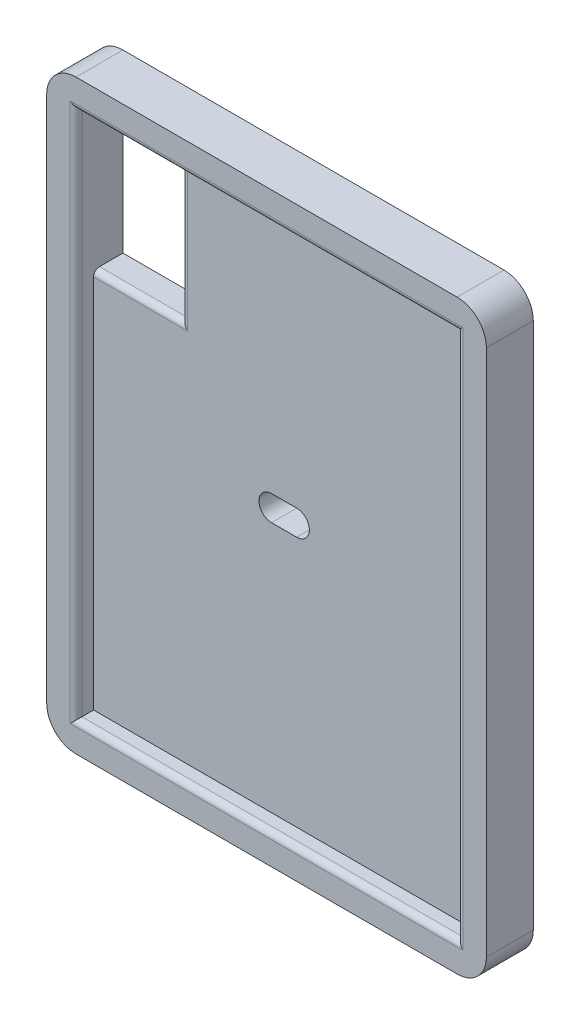
SolidWorks part; units mm, degrees
ref_plane "Front Plane" through (0, 0, 0) normal (1, 0, 0) x (0, 1, 0)
ref_plane "Top Plane" through (0, 0, 0) normal (0, 0, 1) x (0, 1, 0)
ref_plane "Right Plane" through (0, 0, 0) normal (0, 1, 0) x (-1, 0, 0)
sketch "Sketch1" plane through (0, 0, 0) normal (0, 0, 1) x (0, 1, 0)
  line L1 (-50, -37.5) -> (50, -37.5)
  line L2 (-50, -37.5) -> (-50, 37.5)
  line L3 (-50, 37.5) -> (50, 37.5)
  line L4 (50, -37.5) -> (50, 37.5)
  line L5 (-50, -37.5) -> (50, 37.5) construction
  line L6 (-50, 37.5) -> (50, -37.5) construction
  point P0 (0, 0)
  dimension "D1" = 75
  dimension "D2" = 100
extrude "Boss-Extrude1" add sketch "Sketch1" along normal blind 5
sketch "Sketch2" plane through (0, 0, 5) normal (0, 0, 1) x (1, 0, 0)
  line L0 (-37.5, 50) -> (-37.5, -50) construction
  line L1 (-32.5, -45) -> (32.5, -45)
  line L2 (-32.5, -45) -> (-32.5, 45)
  line L3 (-32.5, 45) -> (32.5, 45)
  line L4 (32.5, -45) -> (32.5, 45)
  line L5 (-32.5, -45) -> (32.5, 45) construction
  line L6 (-32.5, 45) -> (32.5, -45) construction
  line L7 (37.5, 50) -> (-37.5, 50) construction
  line L8 (-37.5, 50) -> (37.5, 50)
  line L9 (37.5, 50) -> (37.5, -50)
  line L10 (37.5, -50) -> (37.5, 50) construction
  line L11 (37.5, -50) -> (-37.5, -50)
  line L12 (-37.5, -50) -> (37.5, -50) construction
  line L13 (-37.5, -50) -> (-37.5, 50)
  point P0 (0, 0)
  dimension "D1" = 5
  dimension "D2" = 5
  dimension "D3" = 90
  dimension "D4" = 65
extrude "Boss-Extrude2" add sketch "Sketch2" along normal blind 3
sketch "Sketch3" plane through (0, 0, 5) normal (0, 0, 1) x (1, 0, 0)
  line L0 (-2.15, 0) -> (2.15, 0) construction
  line L1 (-32.5, 45) -> (-17.5, 45)
  line L2 (-32.5, 45) -> (-32.5, 20)
  line L3 (-32.5, 20) -> (-17.5, 20)
  line L4 (-17.5, 45) -> (-17.5, 20)
  line L6 (-2.15, 2.15) -> (2.15, 2.15)
  line L7 (-2.15, -2.15) -> (2.15, -2.15)
  arc A1 (-2.15, 2.15) -> (-2.15, -2.15) centre (-2.15, 0) ccw
  arc A2 (2.15, -2.15) -> (2.15, 2.15) centre (2.15, 0) ccw
  point P7 (-2.5686, 0)
  point P8 (0, 0)
  point P11 (0, 0)
  dimension "D1" = 4.3
  dimension "D2" = 4.3
extrude "Cut-Extrude1" cut sketch "Sketch3" against normal through all
fillet "Fillet1" radius 5 4 edges at (-37.5, 50, 4) (37.5, 50, 4) (37.5, -50, 4) (-37.5, -50, 4)
fillet "Fillet2" radius 1 6 edges at (-17.5, 32.5, 5) (-25, 20, 5) (0, -45, 8) (-32.5, 0, 8) (0, 45, 8) (32.5, 0, 8)
